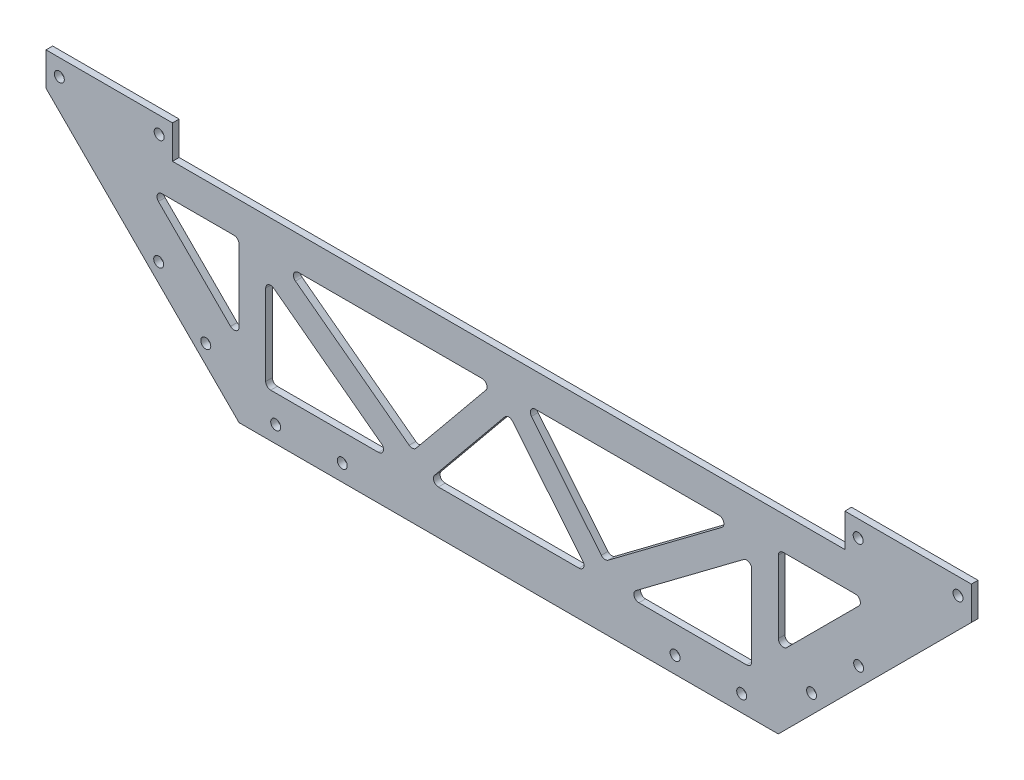
SolidWorks part; units mm, degrees
material "Thornel Mat VMA"
ref_plane "前视基准面" through (0, 0, 0) normal (0, 0, 1) x (1, 0, 0)
ref_plane "上视基准面" through (0, 0, 0) normal (0, 1, 0) x (1, 0, 0)
ref_plane "右视基准面" through (0, 0, 0) normal (1, 0, 0) x (0, 0, -1)
sketch "草图1" plane through (0, 0, 0) normal (0, 0, 1) x (1, 0, 0)
  line L0 (-101, 30) -> (-101, 0)
  line L1 (-101, 0) -> (101, 0)
  line L2 (101, 0) -> (101, 30)
  line L3 (-101, 30) -> (-139, 30)
  line L5 (-81, -58) -> (81, -58)
  line L7 (139, 30) -> (101, 30)
  line L8 (0, 0) -> (0, -58) construction
  line L9 (-135, 25) -> (-105, 25) construction
  line L10 (-135, 25) -> (-135, 5) construction
  line L11 (-135, 5) -> (-105, 5) construction
  line L12 (-105, 25) -> (-105, 5) construction
  line L13 (105, 25) -> (105, 5) construction
  line L14 (135, 5) -> (105, 5) construction
  line L15 (135, 25) -> (135, 5) construction
  line L16 (135, 25) -> (105, 25) construction
  line L17 (-70, -53) -> (-50, -53) construction
  line L18 (70, -53) -> (50, -53) construction
  line L19 (-139, 30) -> (-139, 0)
  line L20 (-139, 0) -> (-81, -58)
  line L21 (81, -58) -> (139, 0)
  line L22 (139, 0) -> (139, 30)
  circle A0 centre (-135, 25) radius 1.5
  circle A1 centre (-105, 25) radius 1.5
  circle A2 centre (-105, 5) radius 1.5
  circle A3 centre (-135, 5) radius 1.5
  circle A4 centre (135, 5) radius 1.5
  circle A5 centre (105, 5) radius 1.5
  circle A6 centre (105, 25) radius 1.5
  circle A7 centre (135, 25) radius 1.5
  circle A8 centre (-70, -53) radius 1.5
  circle A9 centre (-50, -53) radius 1.5
  circle A10 centre (50, -53) radius 1.5
  circle A11 centre (70, -53) radius 1.5
  point P4 (0, 0)
  dimension "D5" = 3
  dimension "D10" = 3
  dimension "D1" = 30
  dimension "D2" = 202
  dimension "D3" = 58
  dimension "D4" = 38
  dimension "D6" = 5
  dimension "D7" = 5
  dimension "D8" = 4
  dimension "D9" = 4
  dimension "D11" = 20
  dimension "D12" = 50
  dimension "D13" = 5
  dimension "D14" = 45
extrude "凸台-拉伸1" add sketch "草图1" along normal blind 2
sketch "草图2" plane through (0, 0, 2) normal (0, 0, 1) x (1, 0, 0)
  line L0 (-105.1421, -28.201) -> (-91, -42.3431) construction
  line L1 (0, 0) -> (0, -58) construction
  line L2 (-81, -58) -> (81, -58) construction
  line L3 (-139, 0) -> (-81, -58) construction
  line L4 (105.1421, -28.201) -> (91, -42.3431) construction
  circle A0 centre (-105.1421, -28.201) radius 1.5
  circle A1 centre (-91, -42.3431) radius 1.5
  circle A2 centre (91, -42.3431) radius 1.5
  circle A3 centre (105.1421, -28.201) radius 1.5
  dimension "D3" = 3
  dimension "D1" = 4
  dimension "D2" = 20
  dimension "D4" = 10
extrude "切除-拉伸1" cut sketch "草图2" against normal through all
sketch "草图3" plane through (0, 0, 2) normal (0, 0, 1) x (1, 0, 0)
  line L0 (139, 0) -> (139, 30) construction
  line L1 (-139, 30) -> (139, 30)
  line L2 (-139, 30) -> (-139, 10)
  line L3 (-139, 10) -> (139, 10)
  line L4 (139, 30) -> (139, 10)
  circle A0 centre (135, 5) radius 1.5 construction
  dimension "D1" = 5
extrude "切除-拉伸2" cut sketch "草图3" against normal through all
sketch "草图4" plane through (0, 0, 2) normal (0, 0, 1) x (1, 0, 0)
  line L0 (-105.2261, -12.5607) -> (-83.5607, -34.2261)
  line L1 (-81, -33.1655) -> (-81, -11.5)
  line L2 (-82.5, -10) -> (-104.1655, -10)
  line L3 (101, 0) -> (-101, 0) construction
  line L4 (-139, 0) -> (-81, -58) construction
  line L5 (0, 0) -> (0, -58) construction
  line L6 (-81, -58) -> (81, -58) construction
  line L10 (-73, -19) -> (-73, -43.2868)
  line L11 (-71.5, -44.7868) -> (-39.1176, -44.7868)
  line L12 (-38.2176, -42.0868) -> (-70.6, -17.8)
  line L13 (-63.1667, -10) -> (-8, -10)
  line L14 (-6.8398, -12.4508) -> (-27.8398, -38.0758)
  line L15 (-29.9, -38.325) -> (-64.0667, -12.7)
  line L20 (29.9, -38.325) -> (64.0667, -12.7)
  line L21 (6.8398, -12.4508) -> (27.8398, -38.0758)
  line L22 (63.1667, -10) -> (8, -10)
  line L23 (38.2176, -42.0868) -> (70.6, -17.8)
  line L24 (71.5, -44.7868) -> (39.1176, -44.7868)
  line L25 (73, -19) -> (73, -43.2868)
  line L26 (82.5, -10) -> (104.1655, -10)
  line L27 (81, -33.1655) -> (81, -11.5)
  line L28 (105.2261, -12.5607) -> (83.5607, -34.2261)
  line L29 (-22.2808, -42.336) -> (-1.1602, -16.5638)
  line L30 (-21.1206, -44.7868) -> (21.1206, -44.7868)
  line L31 (22.2808, -42.336) -> (1.1602, -16.5638)
  arc A4 (-8, -10) -> (-6.8398, -12.4508) centre (-8, -11.5) cw
  arc A5 (-27.8398, -38.0758) -> (-29.9, -38.325) centre (-29, -37.125) cw
  arc A6 (-63.1667, -10) -> (-64.0667, -12.7) centre (-63.1667, -11.5) ccw
  arc A7 (-39.1176, -44.7868) -> (-38.2176, -42.0868) centre (-39.1176, -43.2868) ccw
  arc A8 (-73, -43.2868) -> (-71.5, -44.7868) centre (-71.5, -43.2868) ccw
  arc A9 (-73, -19) -> (-70.6, -17.8) centre (-71.5, -19) cw
  arc A10 (-83.5607, -34.2261) -> (-81, -33.1655) centre (-82.5, -33.1655) ccw
  arc A11 (-81, -11.5) -> (-82.5, -10) centre (-82.5, -11.5) ccw
  arc A12 (-105.2261, -12.5607) -> (-104.1655, -10) centre (-104.1655, -11.5) cw
  arc A13 (105.2261, -12.5607) -> (104.1655, -10) centre (104.1655, -11.5) ccw
  arc A14 (81, -11.5) -> (82.5, -10) centre (82.5, -11.5) cw
  arc A15 (83.5607, -34.2261) -> (81, -33.1655) centre (82.5, -33.1655) cw
  arc A16 (73, -19) -> (70.6, -17.8) centre (71.5, -19) ccw
  arc A17 (73, -43.2868) -> (71.5, -44.7868) centre (71.5, -43.2868) cw
  arc A18 (39.1176, -44.7868) -> (38.2176, -42.0868) centre (39.1176, -43.2868) cw
  arc A19 (63.1667, -10) -> (64.0667, -12.7) centre (63.1667, -11.5) cw
  arc A20 (27.8398, -38.0758) -> (29.9, -38.325) centre (29, -37.125) ccw
  arc A21 (8, -10) -> (6.8398, -12.4508) centre (8, -11.5) ccw
  arc A22 (22.2808, -42.336) -> (21.1206, -44.7868) centre (21.1206, -43.2868) cw
  arc A23 (-22.2808, -42.336) -> (-21.1206, -44.7868) centre (-21.1206, -43.2868) ccw
  arc A24 (-1.1602, -16.5638) -> (1.1602, -16.5638) centre (0, -17.5146) cw
  point P23 (24.2893, -44.7868)
  point P27 (-24.2893, -44.7868)
  point P31 (0, -15.1481)
  point P46 (-67.6667, -10)
  point P51 (-73, -44.7868)
  point P54 (-73, -16)
  point P59 (-81, -10)
  point P89 (81, -10)
  point P90 (73, -16)
  point P91 (73, -44.7868)
  point P92 (67.6667, -10)
  dimension "D7" = 1.5
  dimension "D10" = 1.5
  dimension "D1" = 10
  dimension "D2" = 15
  dimension "D3" = 8
  dimension "D4" = 8
  dimension "D5" = 6
  dimension "D6" = 8
  dimension "D8" = 29
  dimension "D9" = 7
extrude "切除-拉伸3" cut sketch "草图4" against normal through all and the other way through all
